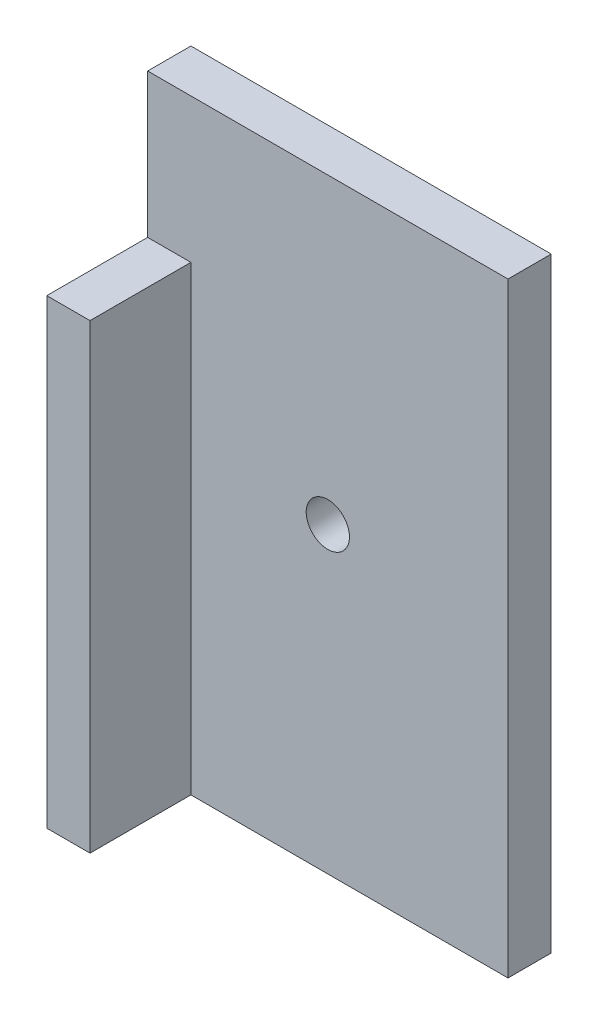
SolidWorks part; units mm, degrees
ref_plane "前视基准面" through (0, 0, 0) normal (0, 0, 1) x (1, 0, 0)
ref_plane "上视基准面" through (0, 0, 0) normal (0, 1, 0) x (1, 0, 0)
ref_plane "右视基准面" through (0, 0, 0) normal (1, 0, 0) x (0, 0, -1)
other "Configuration Table"
sketch "草图1" plane through (0, 0, 0) normal (0, 0, 1) x (1, 0, 0)
  line L0 (0, 0) -> (-50000, 0) construction
  line L1 (-12.5, 21) -> (12.5, 21)
  line L2 (-12.5, 21) -> (-12.5, -21)
  line L3 (-12.5, -21) -> (12.5, -21)
  line L4 (12.5, 21) -> (12.5, -21)
  line L5 (-12.5, 21) -> (12.5, -21) construction
  line L6 (-12.5, -21) -> (12.5, 21) construction
  circle A2 centre (0, 0) radius 1.5
  point P0 (0, 0)
  dimension "D3" = 3
  dimension "D1" = 42
  dimension "D2" = 25
extrude "凸台-拉伸1" add sketch "草图1" along normal blind 3
sketch "草图2" plane through (0, 0, 3) normal (0, 0, 1) x (1, 0, 0)
  line L0 (-12.5, -21) -> (12.5, -21) construction
  line L1 (-12.5, 21) -> (-9.5, 21)
  line L2 (-12.5, 21) -> (-12.5, -21)
  line L3 (-12.5, -21) -> (-9.5, -21)
  line L4 (-9.5, 21) -> (-9.5, -21)
  dimension "D1" = 3
extrude "凸台-拉伸2" add sketch "草图2" along normal blind 7
sketch "草图4" plane through (-9.5, 0, 0) normal (1, 0, 0) x (0, 0, -1)
  line L0 (-3, -21) -> (-3, 21) construction
  line L1 (-10, 21) -> (-3, 21)
  line L2 (-10, 21) -> (-10, 11)
  line L3 (-10, 11) -> (-3, 11)
  line L4 (-3, 21) -> (-3, 11)
  dimension "D1" = 10
extrude "切除-拉伸1" cut sketch "草图4" against normal blind 10
